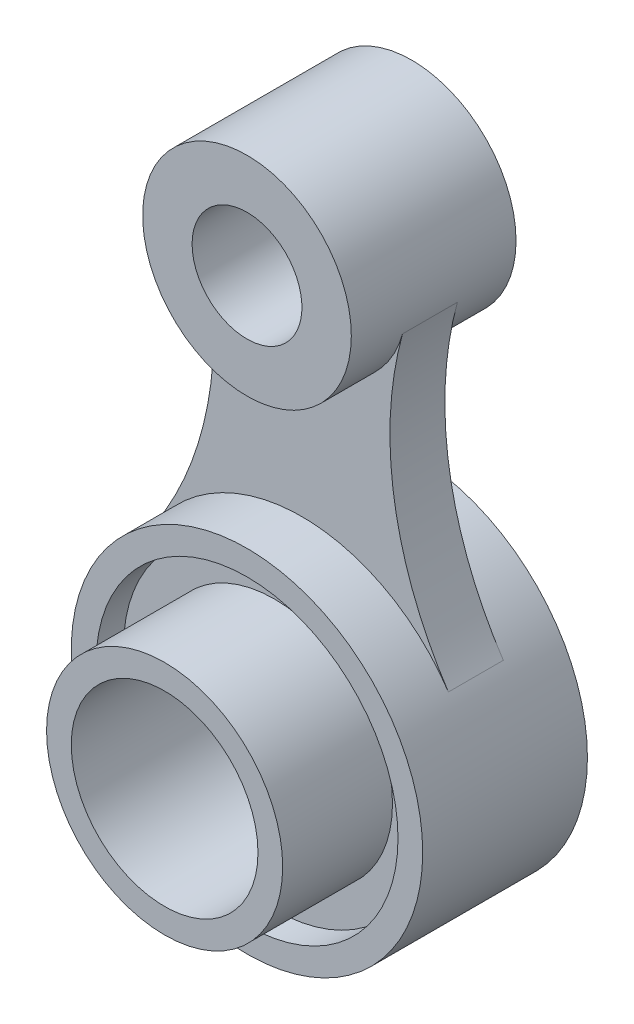
SolidWorks part; units mm, degrees
ref_plane "Front Plane" through (0, 0, 0) normal (0, 0, 1) x (1, 0, 0)
ref_plane "Top Plane" through (0, 0, 0) normal (0, 1, 0) x (1, 0, 0)
ref_plane "Right Plane" through (0, 0, 0) normal (1, 0, 0) x (0, 0, -1)
sketch "Sketch1" plane through (0, 0, 0) normal (0, 0, 1) x (1, 0, 0)
  line L0 (0, 37.5) -> (0, -37.5) construction
  point P4 (0, 0)
  dimension "D1" = 75
sketch "Sketch2" plane through (0, 0, 0) normal (0, 0, 1) x (1, 0, 0)
  circle A0 centre (0, 37.5) radius 19
  circle A1 centre (0, -37.5) radius 32
  dimension "D1" = 38
  dimension "D2" = 64
extrude "Boss-Extrude1" add sketch "Sketch2" along normal blind 30
ref_plane "Plane1" through (0, 0, 10) normal (0, 0, 1) x (1, 0, 0)
sketch "Sketch3" plane through (0, 0, 10) normal (0, 0, 1) x (1, 0, 0)
  arc A0 (-18.3212, 32.4669) -> (18.3212, 32.4669) centre (0, 37.5) ccw
  arc A1 (26.6783, -19.8289) -> (-26.6783, -19.8289) centre (0, -37.5) ccw
  arc A2 (-18.3212, 32.4669) -> (-26.6783, -19.8289) centre (-80.0349, 15.5133) cw
  arc A3 (18.3212, 32.4669) -> (26.6783, -19.8289) centre (80.0349, 15.5133) ccw
  dimension "D1" = 64
  dimension "D2" = 38
  dimension "D3" = 64
extrude "Boss-Extrude2" add sketch "Sketch3" along normal blind 10
ref_plane "Plane2" through (0, 0, 25) normal (0, 0, 1) x (1, 0, 0)
sketch "Sketch4" plane through (0, 0, 25) normal (0, 0, 1) x (1, 0, 0)
  circle A0 centre (0, -37.5) radius 27.5
  dimension "D1" = 55
extrude "Cut-Extrude1" cut sketch "Sketch4" along normal blind 5
sketch "Sketch5" plane through (0, 0, 25) normal (0, 0, 1) x (1, 0, 0)
  circle A0 centre (0, -37.5) radius 21.5
  dimension "D1" = 43
extrude "Boss-Extrude3" add sketch "Sketch5" along normal blind 20
sketch "Sketch6" plane through (0, 0, 0) normal (0, 0, 1) x (1, 0, 0)
  circle A0 centre (0, 37.5) radius 10
  circle A1 centre (0, -37.5) radius 17
  dimension "D1" = 20
  dimension "D2" = 34
extrude "Cut-Extrude2" cut sketch "Sketch6" along normal through all
